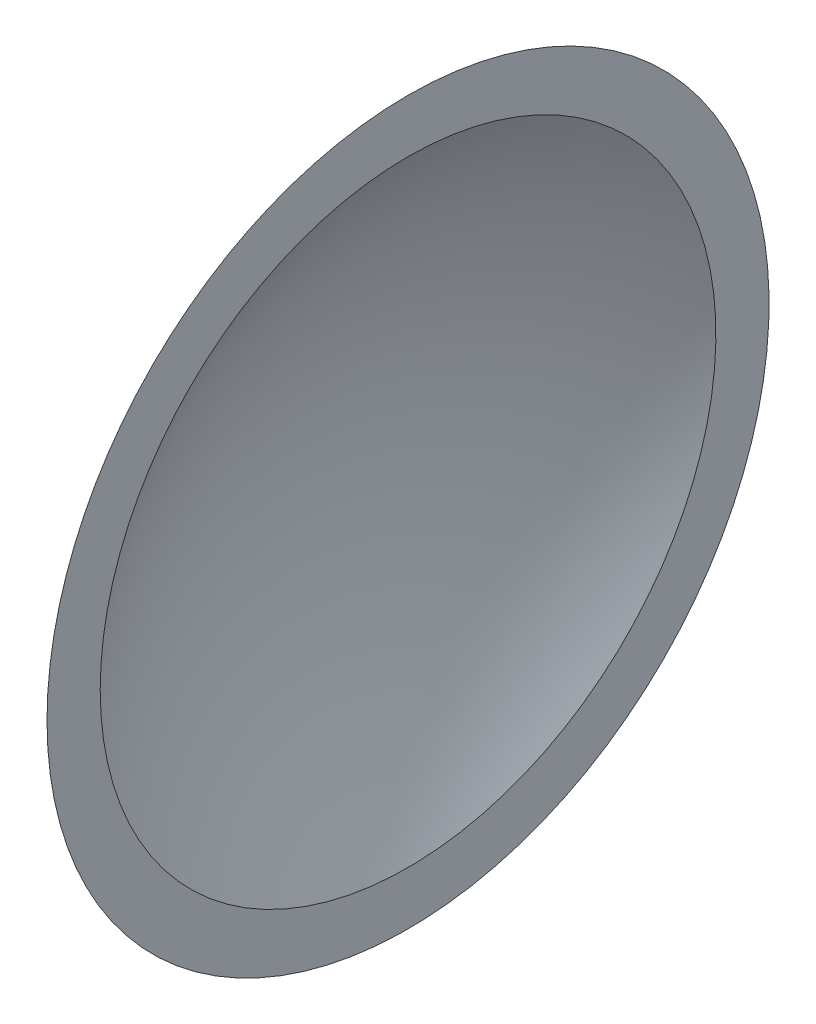
SolidWorks part; units mm, degrees
material "Pure Silver"
ref_plane "Front Plane" through (0, 0, 0) normal (0, 0, 1) x (1, 0, 0)
ref_plane "Top Plane" through (0, 0, 0) normal (0, 1, 0) x (1, 0, 0)
ref_plane "Right Plane" through (0, 0, 0) normal (1, 0, 0) x (0, 0, -1)
sketch "Sketch1" plane through (0, 0, 0) normal (0, 0, 1) x (1, 0, 0)
  line L0 (0, 0.5) -> (0, -0.5) construction
  line L1 (0, 5) -> (0, 0) construction
  line L2 (-4.2633, 0) -> (-4.2633, 2.6123) construction
  line L3 (-5, 0) -> (0, 0) construction
  line L4 (0, 0) -> (20.4, 0) construction
  line L5 (-5.25, 0) -> (-5, 0)
  line L6 (-4.2633, 2.6123) -> (-4.2633, 3.0638)
  line L7 (20.4, 12.5) -> (20.4, -12.5) construction
  line L8 (-4.2633, 2.6123) -> (20.4, -12.5) construction
  line L9 (20.4, -12.5) -> (20.65, -12.5)
  line L10 (20.4, 0) -> (23.4, 0)
  line L11 (23.4, 0) -> (25.4, 0) construction
  line L12 (20.4, 0) -> (20.4, -12.5)
  line L13 (24.4, 12.5) -> (24.4, -12.5) construction
  line L14 (28.4, -12.5) -> (28.15, -12.5)
  line L15 (28.4, 0) -> (28.4, -12.5)
  line L16 (28.4, 0) -> (25.4, 0)
  line L17 (28.4, -12.5) -> (28.4, 12.5) construction
  line L18 (20.4, -12.5) -> (28.4, -12.5) construction
  line L19 (28.4, 0) -> (48.8, 0) construction
  line L20 (48.8, 0) -> (28.4, -12.5) construction
  line L21 (48.8, 0) -> (329.9959, 0) construction
  line L22 (329.9959, 254.635) -> (329.9959, -254.635) construction
  line L23 (679.9959, 310.1741) -> (679.9959, -310.1741) construction
  line L24 (679.9959, 0) -> (729.9959, 0) construction
  line L25 (729.9959, 254.635) -> (729.9959, -254.635)
  line L26 (679.9959, 254.635) -> (679.9959, 264.635)
  line L27 (329.9959, 254.635) -> (329.9959, -254.635)
  line L28 (329.9959, 0) -> (679.9959, 0) construction
  line L29 (679.9959, 254.635) -> (679.9959, -254.635)
  line L30 (679.9959, 310.1741) -> (48.8, 0) construction
  line L31 (329.9959, 254.635) -> (329.9959, 264.635)
  line L32 (329.9959, -254.635) -> (329.9959, -264.635)
  line L33 (679.9959, -254.635) -> (679.9959, -264.635)
  line L34 (679.9959, 254.635) -> (729.9959, 254.635) construction
  line L35 (729.9959, 0) -> (779.9959, 0) construction
  line L36 (779.9959, 254.635) -> (779.9959, -254.635)
  line L37 (729.9959, 254.635) -> (779.9959, 254.635) construction
  line L38 (779.9959, 254.635) -> (779.9959, 264.635)
  line L39 (779.9959, -254.635) -> (779.9959, -264.635)
  line L40 (779.9959, 0) -> (839.9959, 0) construction
  line L41 (839.9959, 0) -> (1095.4391, 0) construction
  line L42 (839.9959, -254.635) -> (839.9959, 254.635)
  line L43 (841.9959, -254.635) -> (841.9959, 254.635)
  line L44 (839.9959, 254.635) -> (839.9959, 264.635)
  line L45 (839.9959, 254.635) -> (841.9959, 254.635) construction
  line L46 (779.9959, 254.635) -> (1095.4391, 0) construction
  line L47 (841.9959, 254.635) -> (841.9959, 264.635)
  line L48 (1094.9959, 32.5) -> (1094.9959, -32.5)
  line L49 (1094.9959, 0) -> (3152.2686, 0) construction
  line L50 (3152.2686, -1435.2155) -> (3152.2686, 1435.2155)
  line L51 (1094.9959, 0) -> (729.9959, 254.635) construction
  line L52 (1094.9959, 0) -> (3152.2686, -1435.2155) construction
  line L53 (839.9959, -254.635) -> (839.9959, -264.635)
  line L54 (841.9959, -254.635) -> (841.9959, -264.635)
  line L55 (839.9959, -254.635) -> (841.9959, -254.635) construction
  line L56 (189.398, 119.0908) -> (189.398, -119.0908)
  line L57 (189.398, 119.0908) -> (189.398, 69.0908) construction
  arc A0 (0, -0.5) -> (0, 0.5) centre (0, 0) ccw construction
  arc A1 (0, 5) -> (-5, 0) centre (0, 0) ccw
  arc A2 (-4.2633, 3.0638) -> (-5.25, 0) centre (0, 0) ccw
  arc A3 (-4.2633, 2.6123) -> (-5, 0) centre (0, 0) ccw construction
  arc A4 (23.4, 0) -> (20.65, -12.5) centre (-6.3841, 0) cw
  arc A5 (25.4, 0) -> (28.15, -12.5) centre (55.1841, 0) ccw
  point P14 (20.4, 0)
  point P21 (24.4, 0)
  point P31 (329.9959, 0)
  point P38 (679.9959, 0)
  point P40 (729.9959, 0)
  point P48 (779.9959, 0)
  point P54 (839.9959, 0)
  point P62 (1094.9959, 0)
  point P64 (679.9959, 0)
  point P67 (189.398, 0)
  point P69 (3152.2686, 0)
  point P75 (189.398, 0)
  dimension "D1" = 1
  dimension "D4" = 0.25
  dimension "D2" = 0.25
  dimension "D3" = 5
  dimension "D5" = 3
  dimension "D6" = 2
  dimension "condenserFocalLength" = 20.4
  dimension "condenserDiameter" = 25
  dimension "D7" = 50
  dimension "D8" = 10
  dimension "D9" = 365
  dimension "fresnelCollectorFocus" = 350
  dimension "D10" = 281.1959
  dimension "D11" = 509.27
  dimension "D12" = 50
  dimension "D13" = 60
  dimension "D14" = 2
  dimension "D16" = 255.4432
  dimension "D17" = 65
  dimension "D19" = 620.3481
  dimension "D20" = 2057.2727
  dimension "D21" = 2870.4309
  dimension "D22" = 34.901
sketch "Sketch4" plane through (0, 0, 0) normal (0, 1, 0) x (1, 0, 0)
  line L0 (0, 0.5) -> (0, -0.5) construction
  line L1 (0, 5) -> (0, 0) construction
  line L2 (-4.2633, 0) -> (-4.2633, 2.6123) construction
  line L3 (-5, 0) -> (0, 0) construction
  line L4 (0, 0) -> (20.4, 0) construction
  line L5 (-5.25, 0) -> (-5, 0)
  line L6 (-4.2633, 2.6123) -> (-4.2633, 3.0638)
  line L7 (20.4, 12.5) -> (20.4, -12.5) construction
  line L8 (-4.2633, 2.6123) -> (20.4, -12.5) construction
  line L9 (20.4, -12.5) -> (20.65, -12.5)
  line L10 (20.4, 0) -> (23.4, 0)
  line L11 (23.4, 0) -> (25.4, 0) construction
  line L12 (20.4, 0) -> (20.4, -12.5)
  line L13 (24.4, 12.5) -> (24.4, -12.5) construction
  line L14 (28.4, -12.5) -> (28.15, -12.5)
  line L15 (28.4, 0) -> (28.4, -12.5)
  line L16 (28.4, 0) -> (25.4, 0)
  line L17 (28.4, -12.5) -> (28.4, 12.5) construction
  line L18 (20.4, -12.5) -> (28.4, -12.5) construction
  line L19 (28.4, 0) -> (48.8, 0) construction
  line L20 (48.8, 0) -> (28.4, -12.5) construction
  line L21 (48.8, 0) -> (329.9959, 0) construction
  line L22 (329.9959, 143.256) -> (329.9959, -143.256) construction
  line L23 (679.9959, 310.1741) -> (679.9959, -310.1741) construction
  line L24 (679.9959, 0) -> (729.9959, 0) construction
  line L25 (729.9959, 143.256) -> (729.9959, -143.256)
  line L26 (679.9959, 143.256) -> (679.9959, 153.256)
  line L27 (329.9959, 143.256) -> (329.9959, -143.256)
  line L28 (329.9959, 0) -> (679.9959, 0) construction
  line L29 (679.9959, 143.256) -> (679.9959, -143.256)
  line L30 (679.9959, 310.1741) -> (48.8, 0) construction
  line L31 (329.9959, 143.256) -> (329.9959, 153.256)
  line L32 (329.9959, -143.256) -> (329.9959, -153.256)
  line L33 (679.9959, -143.256) -> (679.9959, -153.256)
  line L34 (679.9959, 143.256) -> (729.9959, 143.256) construction
  line L35 (729.9959, 0) -> (779.9959, 0) construction
  line L36 (779.9959, 143.256) -> (779.9959, -143.256)
  line L37 (729.9959, 143.256) -> (779.9959, 143.256) construction
  line L38 (779.9959, 143.256) -> (779.9959, 153.256)
  line L39 (779.9959, -143.256) -> (779.9959, -153.256)
  line L40 (779.9959, 0) -> (839.9959, 0) construction
  line L41 (839.9959, 0) -> (1095.4391, 0) construction
  line L42 (839.9959, -143.256) -> (839.9959, 143.256)
  line L43 (841.9959, -143.256) -> (841.9959, 143.256)
  line L44 (839.9959, 143.256) -> (839.9959, 153.256)
  line L45 (839.9959, 143.256) -> (841.9959, 143.256) construction
  line L46 (779.9959, 143.256) -> (1095.4391, 0) construction
  line L47 (841.9959, 143.256) -> (841.9959, 153.256)
  line L48 (1094.9959, 32.5) -> (1094.9959, -32.5)
  line L49 (1094.9959, 0) -> (3152.2686, 0) construction
  line L50 (3152.2686, -807.4429) -> (3152.2686, 807.4429)
  line L51 (1094.9959, 0) -> (729.9959, 143.256) construction
  line L52 (1094.9959, 0) -> (3152.2686, -807.4429) construction
  line L53 (839.9959, -143.256) -> (839.9959, -153.256)
  line L54 (841.9959, -143.256) -> (841.9959, -153.256)
  line L55 (839.9959, -143.256) -> (841.9959, -143.256) construction
  line L56 (189.398, 119.0908) -> (189.398, -119.0908)
  line L57 (189.398, 119.0908) -> (189.398, 69.0908) construction
  arc A0 (0, -0.5) -> (0, 0.5) centre (0, 0) ccw construction
  arc A1 (0, 5) -> (-5, 0) centre (0, 0) ccw
  arc A2 (-4.2633, 3.0638) -> (-5.25, 0) centre (0, 0) ccw
  arc A3 (-4.2633, 2.6123) -> (-5, 0) centre (0, 0) ccw construction
  arc A4 (23.4, 0) -> (20.65, -12.5) centre (-6.3841, 0) cw
  arc A5 (25.4, 0) -> (28.15, -12.5) centre (55.1841, 0) ccw
  point P14 (20.4, 0)
  point P21 (24.4, 0)
  point P31 (329.9959, 0)
  point P38 (679.9959, 0)
  point P40 (729.9959, 0)
  point P48 (779.9959, 0)
  point P54 (839.9959, 0)
  point P62 (1094.9959, 0)
  point P64 (679.9959, 0)
  point P67 (189.398, 0)
  point P69 (3152.2686, 0)
  point P75 (189.398, 0)
  dimension "D1" = 1
  dimension "D4" = 0.25
  dimension "D2" = 0.25
  dimension "D3" = 5
  dimension "D5" = 3
  dimension "D6" = 2
  dimension "condenserFocalLength" = 20.4
  dimension "condenserDiameter" = 25
  dimension "D7" = 50
  dimension "D8" = 10
  dimension "D9" = 281.1959
  dimension "D10" = 350
  dimension "D11" = 286.512
  dimension "D12" = 50
  dimension "D13" = 60
  dimension "D14" = 2
  dimension "D15" = 365
  dimension "D16" = 255.4432
  dimension "D17" = 65
  dimension "D19" = 620.3481
  dimension "D20" = 2057.2727
  dimension "D21" = 1614.8858
  dimension "D22" = 21.429
revolve "Revolve1" add sketch "Sketch1" angle 360 about L3
equation "\"colF2\"= 787.4"
equation "\"colF1\"= 787.4"
equation "\"colD\"= 350"
equation "\"colEFL\"= ( ( 1 / \"colF2\" ) + 1 / ( \"colF1\" ) - \"colD\" / ( \"colF2\" * \"colF1\" ) ) ^ - 1"
equation "\"fresnelCollectorFocus@Sketch1\"=\"colD\""
equation "\"D13@Sketch1\"=\"conD\""
equation "\"colBFL\"= ( ( \"colF2\" * ( \"colD\" - \"colF1\" ) ) / ( \"colD\" - ( \"colF1\" + \"colF2\" ) ) )"
equation "\"conD\"= 60"
equation "\"conF1\"= 787.4"
equation "\"conF2\"= 787.4/2"
equation "\"conEFL\"= ( ( - 1 * \"conF1\" * \"conF2\" ) / ( \"conD\" - \"conF1\" - \"conF2\" ) )"
equation "\"conBFL\"= ( ( \"conF2\" * ( \"conD\" - \"conF1\" ) ) / ( \"conD\" - ( \"conF1\" + \"conF2\" ) ) )"
equation "\"D16@Sketch1\"=\"conBFL\""
equation "\"condenserEFL\"= 20.40"
equation "\"condenserDiameter\"= 25"
equation "\"colBEAM\"= \"condenserDiameter\" * ( \"colEFL\" / \"condenserEFL\" )"
equation "\"D19@Sketch1\"=\"colBEAM\""
equation "\"projectorFL\"= 310'Condition: LCD Distance > projectorFL"
equation "\"LCD_Distance\"= 365"
equation "\"imageDistance\"= ( ( \"LCD_Distance\" * \"projectorFL\" ) / ( \"LCD_Distance\" - \"projectorFL\" ) )"
equation "\"D20@Sketch1\" = \"imageDistance\""
equation "\"D10@Sketch1\" = \"colBFL\""
equation "\"condenserFocalLength@Sketch1\"=\"condenserEFL\""
equation "\"condenserDiameter@Sketch1\"=\"condenserDiameter\""
equation "\"D9@Sketch4\"=\"colBFL\""
equation "\"D10@Sketch4\"=\"colD\""
equation "\"condenserFocalLength@Sketch4\"=\"condenserEFL\""
equation "\"condenserDiameter@Sketch4\"=\"condenserDiameter\""
equation "\"D19@Sketch4\"=\"colBEAM\""
equation "\"D13@Sketch4\"=\"conD\""
equation "\"D16@Sketch4\"=\"conBFL\""
equation "\"D20@Sketch4\" = \"imageDistance\""
equation "\"D15@Sketch4\"=\"LCD_Distance\""
equation "\"D9@Sketch1\"=\"LCD_Distance\""
